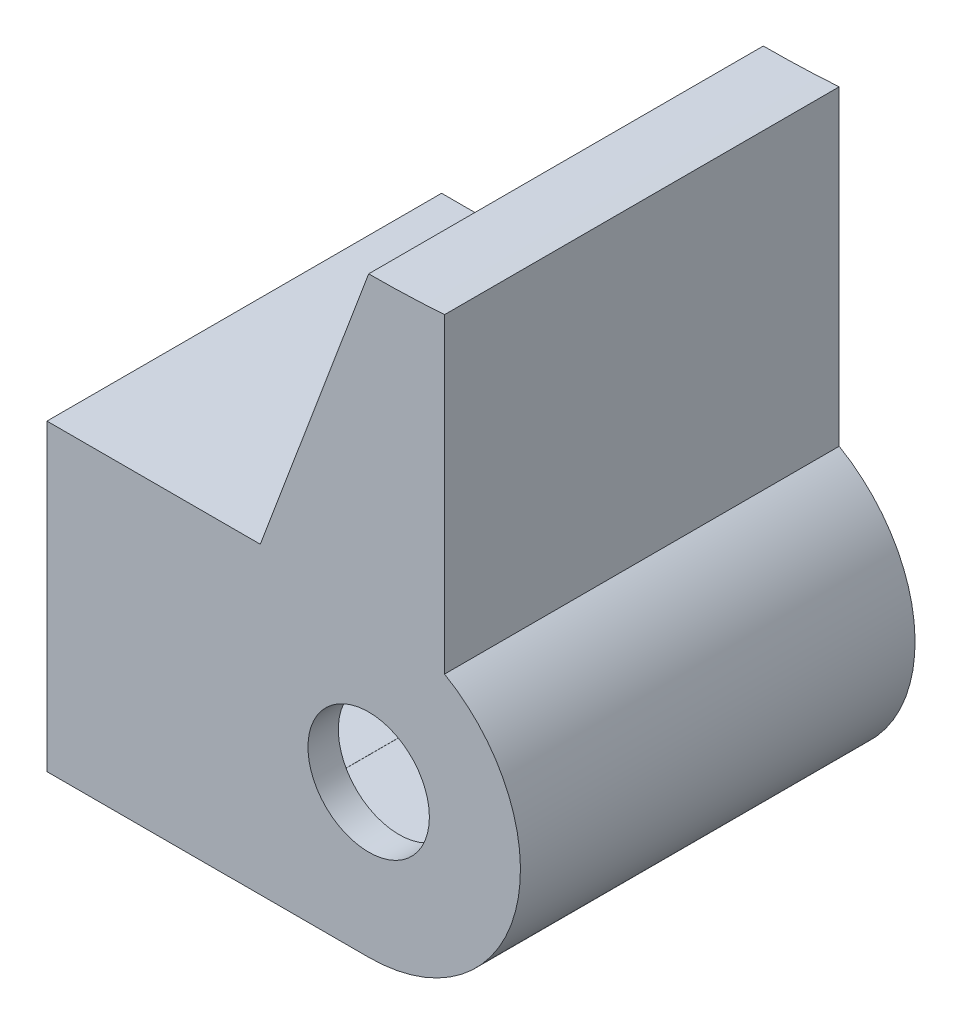
SolidWorks part; units mm, degrees
ref_plane "前视基准面" through (0, 0, 0) normal (0, 0, 1) x (1, 0, 0)
ref_plane "上视基准面" through (0, 0, 0) normal (0, 1, 0) x (1, 0, 0)
ref_plane "右视基准面" through (0, 0, 0) normal (1, 0, 0) x (0, 0, -1)
sketch "草图1" plane through (0, 0, 0) normal (0, 0, 1) x (1, 0, 0)
  line L0 (574.0175, -50) -> (620, -50)
  line L1 (620, 0) -> (690.2817, 121.7314) construction
  line L2 (620, 117.9968) -> (620, -124.5038) construction
  line L3 (584.2888, 50) -> (514.0175, 50)
  line L4 (574.0175, -50) -> (573.9465, -50.0248)
  line L5 (620, 0) -> (620, 510) construction
  line L6 (645, 43.3013) -> (645, 145.8572)
  line L8 (584.2888, 50) -> (620, 145)
  line L9 (514.0175, 22.6759) -> (514.0175, -50.0248)
  line L10 (514.0175, -50.0248) -> (573.9465, -50.0248)
  line L11 (573.9465, -50.0248) -> (573.928, -50.8381)
  line L12 (514.0175, 50) -> (514.0175, 22.6759)
  arc A0 (620, -50) -> (645, 43.3013) centre (620, 0) ccw
  arc A1 (620, -50) -> (645, 43.3013) centre (620, 0) ccw
  arc A3 (620, 145) -> (645, 145.8572) centre (620, 510) ccw
  dimension "D1" = 30
extrude "凸台-拉伸1" add sketch "草图1" along normal blind 130 contours A3 L8 L3 L12 L9 L10 L4 L0 A1 L6
shell "抽壳2" thickness 10
sketch "草图2" plane through (0, 0, 0) normal (0, 0, -1) x (-1, 0, 0)
  line L1 (-514.0175, 50) -> (-514.0175, -50.0248) construction
  line L2 (-524.0175, 40) -> (-514.0175, 40)
  line L3 (-524.0175, 40) -> (-524.0175, -40.0248)
  line L4 (-524.0175, -40.0248) -> (-514.0175, -40.0248)
  line L5 (-514.0175, 40) -> (-514.0175, -40.0248)
extrude "切除-拉伸1" cut sketch "草图2" against normal blind 120
sketch "草图3" plane through (0, 0, 130) normal (0, 0, 1) x (1, 0, 0)
  circle A0 centre (620, 0) radius 20
extrude "切除-拉伸2" cut sketch "草图3" against normal blind 10
